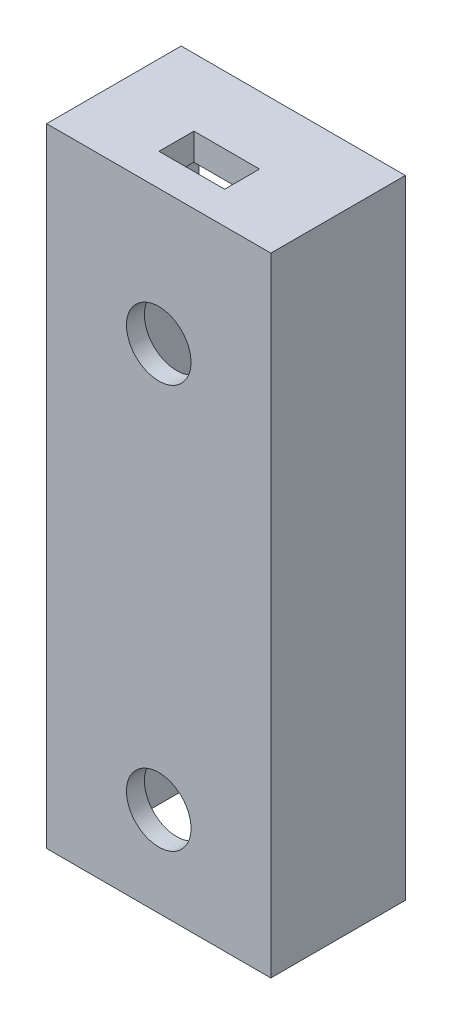
SolidWorks part; units mm, degrees
ref_plane "Front Plane" through (0, 0, 0) normal (0, 0, 1) x (1, 0, 0)
ref_plane "Top Plane" through (0, 0, 0) normal (0, 1, 0) x (1, 0, 0)
ref_plane "Right Plane" through (0, 0, 0) normal (1, 0, 0) x (0, 0, -1)
sketch "Sketch1" plane through (0, 0, 0) normal (0, 0, 1) x (1, 0, 0)
  line L0 (-12.5, -35) -> (12.5, -35)
  line L1 (-12.5, -35) -> (-12.5, 35)
  line L2 (12.5, -35) -> (12.5, 35)
  line L3 (-12.5, 35) -> (12.5, 35)
  line L4 (-12.5, -35) -> (12.5, 35) construction
  line L5 (12.5, -35) -> (-12.5, 35) construction
  point P1 (0, 0)
  dimension "D1" = 70
  dimension "D2" = 25
extrude "Boss-Extrude1" add sketch "Sketch1" against normal blind 15
sketch "Sketch2" plane through (0, 35, 0) normal (0, 1, 0) x (1, 0, 0)
  line L4 (12.5, 15) -> (-12.5, 15) construction
  line L5 (-10.5, 15) -> (10.5, 15)
  line L6 (-10.5, 15) -> (-10.5, 2)
  line L7 (-10.5, 2) -> (10.5, 2)
  line L8 (10.5, 15) -> (10.5, 2)
  line L9 (-12.5, 15) -> (-12.5, 0) construction
  line L10 (12.5, 15) -> (12.5, 0) construction
  line L11 (12.5, 0) -> (-12.5, 0) construction
  dimension "D1" = 2
  dimension "D2" = 2
  dimension "D3" = 2
extrude "Cut-Extrude1" cut sketch "Sketch2" against normal up to next
sketch "Sketch4" plane through (0, 35, 0) normal (0, 1, 0) x (1, 0, 0)
  line L1 (-12.5, 0) -> (12.5, 0)
  line L2 (-12.5, 0) -> (-12.5, 15)
  line L3 (-12.5, 15) -> (12.5, 15)
  line L4 (12.5, 0) -> (12.5, 15)
  line L5 (-3.5678, 3.5945) -> (3.7531, 3.5945)
  line L6 (-3.5678, 3.5945) -> (-3.5678, 7.4866)
  line L7 (-3.5678, 7.4866) -> (3.7531, 7.4866)
  line L8 (3.7531, 3.5945) -> (3.7531, 7.4866)
extrude "Boss-Extrude2" add sketch "Sketch4" against normal blind 3 contours L5 L8 L7 L6 | L2 L1 L4 L3
sketch "Sketch5" plane through (0, 0, -2) normal (0, 0, -1) x (-1, 0, 0)
  line L0 (-12.5, 35) -> (12.5, 35) construction
  line L1 (10.5, -35) -> (-10.5, -35) construction
  line L2 (-12.5, -35) -> (-12.5, 35) construction
  line L3 (12.5, 35) -> (12.5, -35) construction
  circle A0 centre (0, 20) radius 3.6
  circle A1 centre (0, -25) radius 3.6
  point P8 (0, -35)
  point P9 (0, 0)
  dimension "D1" = 7.2
  dimension "D2" = 12.5
  dimension "D6" = 7.2
  dimension "D3" = 15
  dimension "D4" = 10
  dimension "D5" = 12.5
extrude "Cut-Extrude3" cut sketch "Sketch5" against normal up to next
